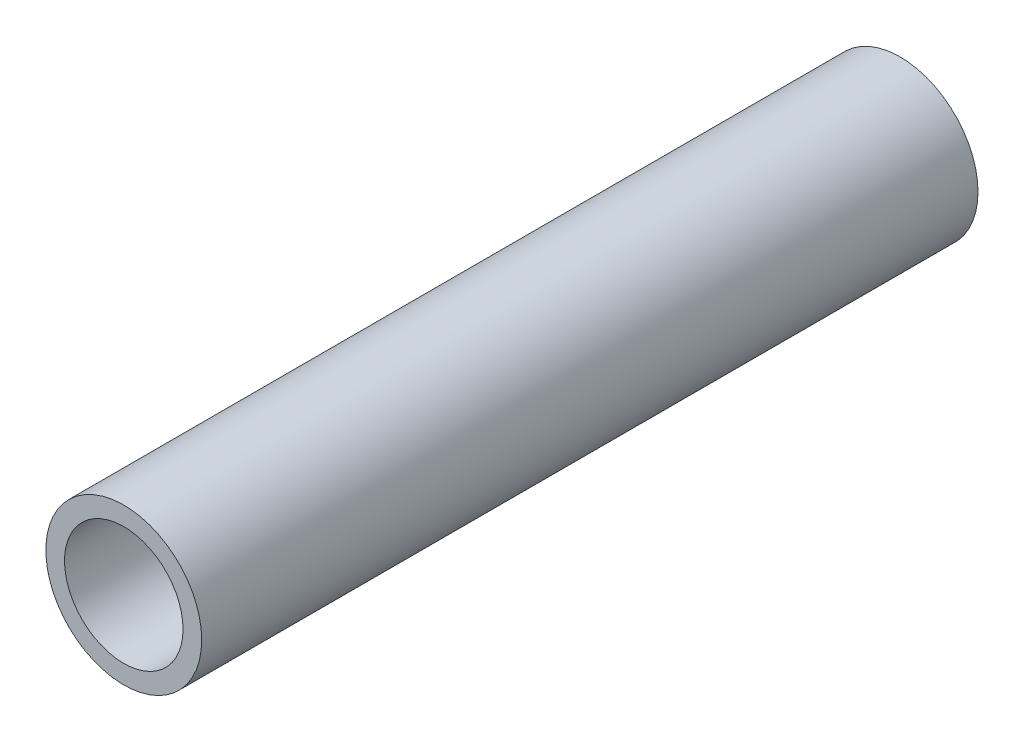
SolidWorks part; units mm, degrees
material "Plain Carbon Steel"
ref_plane "Front Plane" through (0, 0, 0) normal (0, 0, 1) x (1, 0, 0)
ref_plane "Top Plane" through (0, 0, 0) normal (0, 1, 0) x (1, 0, 0)
ref_plane "Right Plane" through (0, 0, 0) normal (1, 0, 0) x (0, 0, -1)
sketch "Sketch1" plane through (0, 0, 0) normal (0, 0, 1) x (1, 0, 0)
  circle A0 centre (0, 0) radius 12.7
  circle A1 centre (0, 0) radius 16.7005
extrude "Boss-Extrude1" add sketch "Sketch1" along normal blind 166.37
